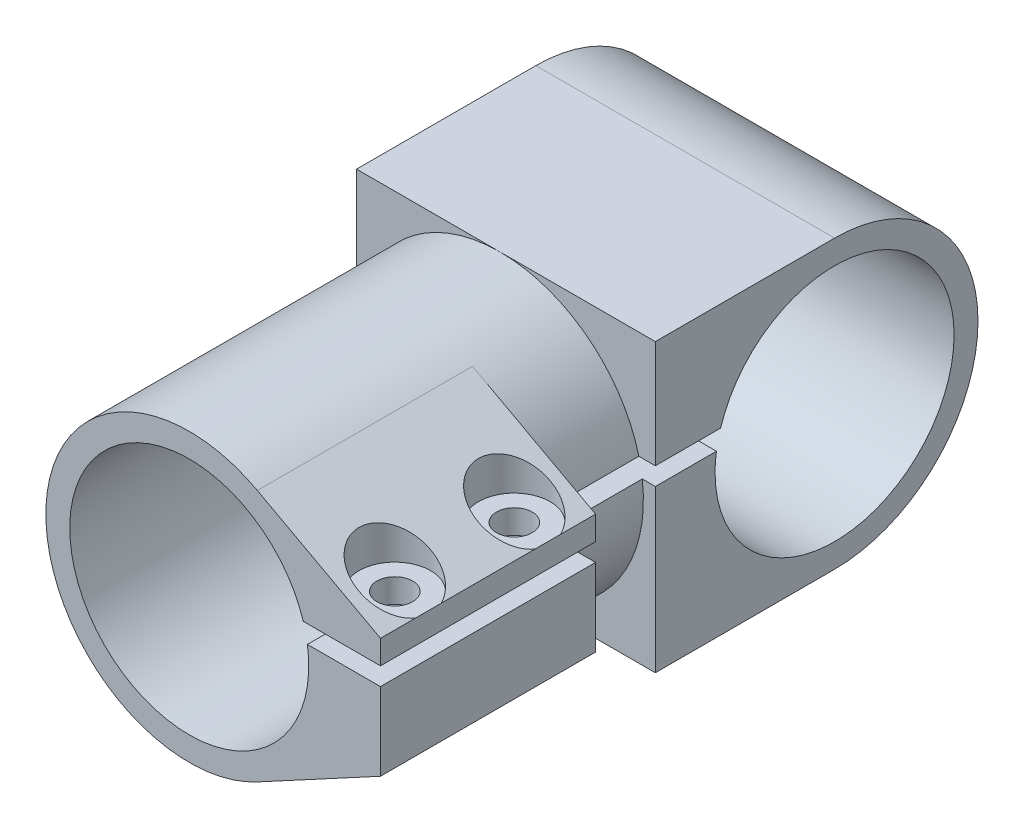
SolidWorks part; units mm, degrees
ref_plane "Plan de face" through (0, 0, 0) normal (0, 0, 1) x (1, 0, 0)
ref_plane "Plan de dessus" through (0, 0, 0) normal (0, 1, 0) x (1, 0, 0)
ref_plane "Plan de droite" through (0, 0, 0) normal (1, 0, 0) x (0, 0, -1)
sketch "Esquisse1" plane through (0, 0, 0) normal (0, 0, 1) x (1, 0, 0)
  line L0 (5.7001, 10.5598) -> (16, 5)
  line L1 (16, 5) -> (16, -5) construction
  line L2 (16, -5) -> (5.7001, -10.5598)
  line L3 (0, 0) -> (12.0938, 0) construction
  line L4 (16, 5) -> (16, 3)
  line L5 (16, 3) -> (9.5394, 3)
  line L6 (16, 1.5) -> (16, -5)
  line L7 (16, 1.5) -> (9.8869, 1.5)
  circle A0 centre (0, 0) radius 10 construction
  circle A1 centre (0, 0) radius 12 construction
  arc A2 (5.7001, 10.5598) -> (5.7001, -10.5598) centre (0, 0) ccw
  arc A3 (9.5394, 3) -> (9.8869, 1.5) centre (0, 0) ccw
  dimension "D1" = 2
  dimension "D2" = 20
  dimension "D3" = 16
  dimension "D4" = 10
  dimension "D5" = 1.5
  dimension "D6" = 2
extrude "Boss.-Extru.1" add sketch "Esquisse1" along normal blind 26
ref_plane "Plan1" through (-12, 0, 0) normal (-1, 0, 0) x (0, 0, 1)
sketch "Esquisse2" plane through (-12, 0, 0) normal (1, 0, 0) x (0, 0, -1)
  line L0 (0, 12) -> (0, -12) construction
  line L1 (0, -12) -> (15, -12)
  line L2 (15, -12) -> (15, 12) construction
  line L3 (15, 12) -> (0, 12)
  line L4 (0, 0) -> (15, 0) construction
  line L5 (0, 12) -> (0, 3)
  line L6 (0, 1.5) -> (0, -12)
  line L7 (0, 3) -> (5.4606, 3)
  line L8 (0, 1.5) -> (5.1131, 1.5)
  arc A0 (15, 12) -> (15, -12) centre (15, 0) cw
  circle A1 centre (15, 0) radius 10 construction
  arc A2 (5.4606, 3) -> (5.1131, 1.5) centre (15, 0) cw
  point P7 (15, 0)
  dimension "D1" = 20
  dimension "D2" = 2
  dimension "D3" = 15
extrude "Boss.-Extru.4" add sketch "Esquisse2" along normal blind 25
sketch "Esquisse5" plane through (0, 0, 0) normal (0, 0, 1) x (1, 0, 0)
  circle A0 centre (0, 0) radius 12
  circle A1 centre (0, 0) radius 17.6918
  arc A2 (0, 12) -> (-11.619, 3) centre (0, 0) ccw construction
extrude "Enlèv. mat.-Extru.2" cut sketch "Esquisse5" along normal blind 8
sketch "Esquisse4" plane through (0, 0, 26) normal (0, 0, 1) x (1, 0, 0)
  line B0 (6.7398, -9.9285) -> (14, -5)
  line B1 (14, -5) -> (14, 1.5)
  line B2 (14, 1.5) -> (9.8869, 1.5)
  line B3 (9.5394, 3) -> (14, 3)
  line B4 (14, 3) -> (14, 5)
  line B5 (14, 5) -> (6.7398, 9.9285)
  arc B6 (6.7398, 9.9285) -> (6.7398, -9.9285) centre (0, 0) ccw
  arc B7 (9.5394, 3) -> (9.8869, 1.5) centre (0, 0) ccw
sketch_block_instance "Bloc1-1"
sketch_block "Bloc1"
ref_plane "Plan2" through (0, 3, 0) normal (0, -1, 0) x (-1, 0, 0)
sketch "Esquisse6" plane through (0, 3, 0) normal (0, -1, 0) x (-1, 0, 0)
  line L0 (-13.2, -12) -> (-13.2, -22) construction
  line L1 (-16, -26) -> (-16, -8) construction
  line L2 (-16, -17) -> (-13.2, -17) construction
  line L3 (-16, -26) -> (-16, -8) construction
  circle A0 centre (-13.2, -12) radius 3
  circle A1 centre (-13.2, -22) radius 3
  dimension "D2" = 6
  dimension "D1" = 2.8
  dimension "D3" = 10
extrude "Enlèv. mat.-Extru.3" cut sketch "Esquisse6" against normal through all from offset 2 offset against normal yes
sketch "Esquisse7" plane through (0, 5, 0) normal (0, 1, 0) x (1, 0, 0)
  circle A0 centre (13.2, -12) radius 1.5
  circle A1 centre (13.2, -22) radius 1.5
  dimension "D1" = 3
extrude "Enlèv. mat.-Extru.4" cut sketch "Esquisse7" against normal up to vertex (2 mm away)
sketch "Esquisse8" plane through (0, 1.5, 0) normal (0, 1, 0) x (1, 0, 0)
  circle A0 centre (13.2, -12) radius 1.2
  circle A1 centre (13.2, -22) radius 1.2
  dimension "D1" = 2.4
extrude "Enlèv. mat.-Extru.5" cut sketch "Esquisse8" against normal through all and the other way through all
sketch "Esquisse9" plane through (-12, 0, 0) normal (-1, 0, 0) x (0, 0, 1)
  line L0 (-15, 12) -> (0, 12)
  line L1 (0, 12) -> (0, -12)
  line L2 (0, -12) -> (-15, -12)
  circle A0 centre (-15, 0) radius 10
  arc A1 (-15, 12) -> (-15, -12) centre (-15, 0) ccw
  arc A2 (-5.4606, 3) -> (-5.1131, 1.5) centre (-15, 0) ccw construction
extrude "Boss.-Extru.5" add sketch "Esquisse9" against normal blind 12.5
